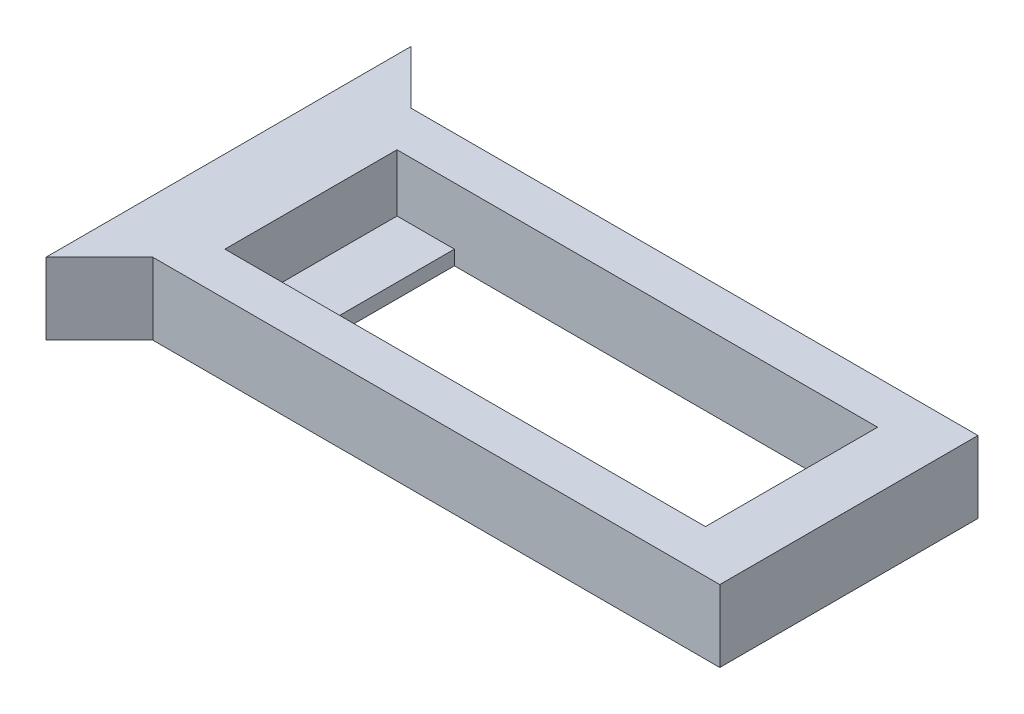
SolidWorks part; units mm, degrees
ref_plane "Front Plane" through (0, 0, 0) normal (0, 0, 1) x (1, 0, 0)
ref_plane "Top Plane" through (0, 0, 0) normal (0, 1, 0) x (1, 0, 0)
ref_plane "Right Plane" through (0, 0, 0) normal (1, 0, 0) x (0, 0, -1)
sketch "Sketch1" plane through (0, 0, 0) normal (0, 0, 1) x (1, 0, 0)
  line L3 (21.625, -5.0081) -> (21.625, 0)
  line L4 (21.625, 0) -> (-21.625, 0)
  line L5 (-21.625, 0) -> (-21.625, -5.0081)
  line L8 (-21.625, -5.0081) -> (21.625, -5.0081)
  point P0 (0, 0)
  dimension "D1" = 43.25
extrude "Boss-Extrude1" add sketch "Sketch1" along normal blind 18
sketch "Sketch2" plane through (0, 0, 0) normal (0, 1, 0) x (1, 0, 0)
  line L0 (21.625, -18) -> (21.625, 0) construction
  line L1 (17.625, -3) -> (-15.875, -3)
  line L2 (17.625, -3) -> (17.625, -15)
  line L3 (17.625, -15) -> (-15.875, -15)
  line L4 (-15.875, -3) -> (-15.875, -15)
  line L5 (17.625, -3) -> (-15.875, -15) construction
  line L6 (17.625, -15) -> (-15.875, -3) construction
  line L7 (21.625, 0) -> (-21.625, 0) construction
  circle A0 centre (6.925, -9) radius 2.325 construction
  point P0 (0.875, -9)
  dimension "D5" = 4.65
  dimension "D6" = 4
  dimension "D1" = 33.5
  dimension "D2" = 12
  dimension "D3" = 10.7
  dimension "D4" = 3
extrude "Cut-Extrude1" cut sketch "Sketch2" against normal blind 4
sketch "Sketch3" plane through (0, -4, 0) normal (0, 1, 0) x (1, 0, 0)
  line L0 (-15.875, -15) -> (17.625, -15) construction
  line L1 (-11.875, -3) -> (13.625, -3)
  line L2 (-11.875, -3) -> (-11.875, -15)
  line L3 (-11.875, -15) -> (13.625, -15)
  line L4 (13.625, -3) -> (13.625, -15)
  line L5 (-11.875, -3) -> (13.625, -15) construction
  line L6 (-11.875, -15) -> (13.625, -3) construction
  line L7 (17.625, -3) -> (-15.875, -3) construction
  line L9 (17.625, -15) -> (17.625, -3) construction
  line L10 (-15.875, -3) -> (-15.875, -15) construction
  point P0 (0.875, -9)
  dimension "D1" = 4
  dimension "D2" = 4
extrude "Cut-Extrude2" cut sketch "Sketch3" against normal up to next
sketch "Sketch4" plane through (0, -4, 0) normal (0, 1, 0) x (1, 0, 0)
  line L0 (13.625, -15) -> (13.625, -3) construction
  line L1 (18.625, -6.5) -> (13.625, -6.5)
  line L2 (18.625, -6.5) -> (18.625, -11.5)
  line L3 (18.625, -11.5) -> (13.625, -11.5)
  line L4 (13.625, -6.5) -> (13.625, -11.5)
  line L5 (18.625, -6.5) -> (13.625, -11.5) construction
  line L6 (18.625, -11.5) -> (13.625, -6.5) construction
  point P0 (16.125, -9)
  point P9 (13.625, -9)
  dimension "D1" = 5
  dimension "D2" = 5
extrude "Cut-Extrude3" cut sketch "Sketch4" against normal up to next
sketch "Sketch5" plane through (0, 0, 0) normal (0, 1, 0) x (1, 0, 0)
  line L0 (-21.625, 0) -> (-21.625, 3.7216)
  line L1 (-21.625, 3.7216) -> (-17.9034, 0)
  line L2 (21.625, 0) -> (-21.625, 0) construction
  line L3 (-17.9034, 0) -> (-21.625, 0)
  line L4 (21.625, -9) -> (-21.625, -9) construction
  line L5 (21.625, -18) -> (21.625, 0) construction
  line L6 (-21.625, -18) -> (-21.625, 0) construction
  line L7 (-17.9034, -18) -> (-21.625, -18)
  line L8 (-21.625, -21.7216) -> (-17.9034, -18)
  line L9 (-21.625, -18) -> (-21.625, -21.7216)
  dimension "D1" = 45
extrude "Boss-Extrude2" add sketch "Sketch5" against normal up to surface (5.0081 mm away) up to face at (8.5, -5.0081, 9)
